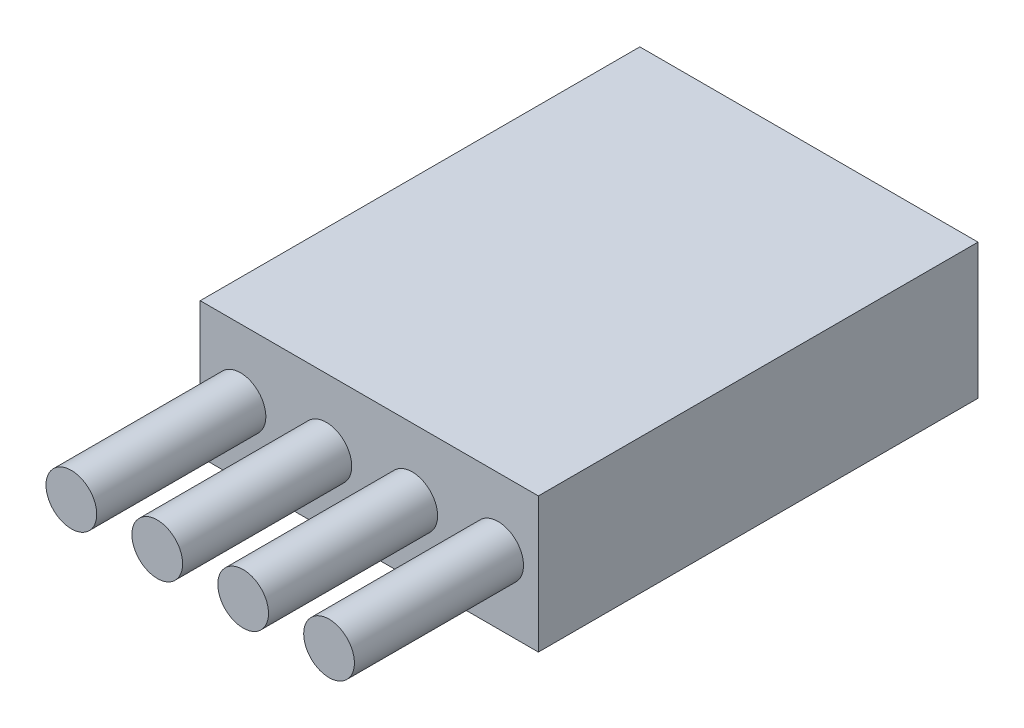
SolidWorks part; units mm, degrees
ref_plane "Спереди" through (0, 0, 0) normal (0, 0, 1) x (1, 0, 0)
ref_plane "Сверху" through (0, 0, 0) normal (0, 1, 0) x (1, 0, 0)
ref_plane "Справа" through (0, 0, 0) normal (1, 0, 0) x (0, 0, -1)
sketch "Sketch1" plane through (0, 0, 0) normal (0, 1, 0) x (1, 0, 0)
  line L1 (-5, -6.5) -> (5, -6.5)
  line L2 (-5, -6.5) -> (-5, 6.5)
  line L3 (-5, 6.5) -> (5, 6.5)
  line L4 (5, -6.5) -> (5, 6.5)
  line L5 (-5, -6.5) -> (5, 6.5) construction
  line L6 (-5, 6.5) -> (5, -6.5) construction
  point P0 (0, 0)
  dimension "D1" = 10
  dimension "D2" = 13
extrude "Boss-Extrude1" add sketch "Sketch1" along normal blind 4
sketch "Sketch2" plane through (0, 0, 6.5) normal (0, 0, 1) x (1, 0, 0)
  line L0 (-5, 2) -> (5.9956, 2) construction
  line L1 (-5, 4) -> (-5, 0) construction
  circle A0 centre (-3.81, 2) radius 0.75
  circle A4 centre (-1.27, 2) radius 0.75
  circle A5 centre (1.27, 2) radius 0.75
  circle A6 centre (3.81, 2) radius 0.75
  point P5 (-4.56, 2)
  point P13 (4.56, 2)
  point P16 (0, 0)
  dimension "D1" = 1.5
  dimension "D3" = 9.12
  dimension "D4" = 0.44
  dimension "D2" = 4
extrude "Boss-Extrude2" add sketch "Sketch2" along normal blind 5
